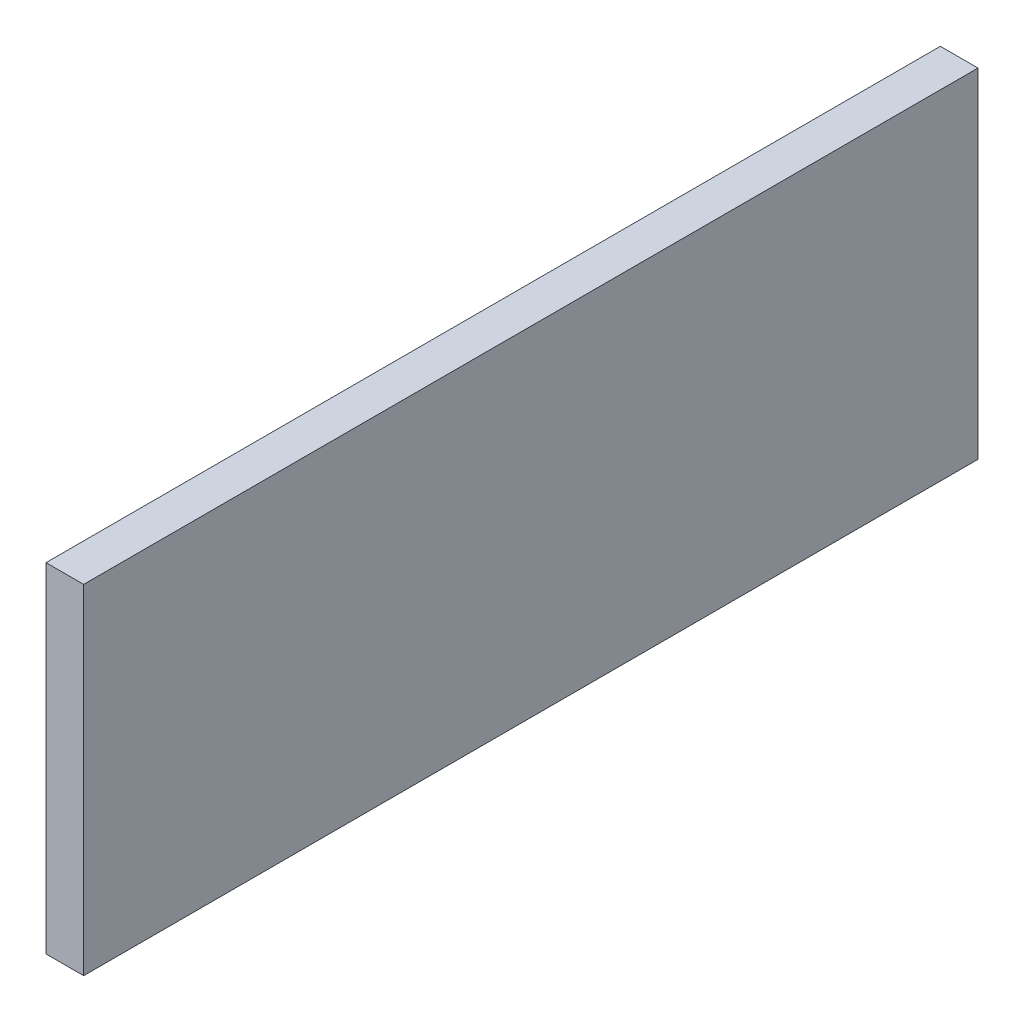
SolidWorks part; units mm, degrees
ref_plane "Front Plane" through (0, 0, 0) normal (0, 0, 1) x (1, 0, 0)
ref_plane "Top Plane" through (0, 0, 0) normal (0, 1, 0) x (1, 0, 0)
ref_plane "Right Plane" through (0, 0, 0) normal (1, 0, 0) x (0, 0, -1)
sketch "Sketch2" plane through (0, 0, 0) normal (1, 0, 0) x (0, 0, -1)
  line L1 (0, 0) -> (50, 0)
  line L2 (0, 0) -> (0, 22.5)
  line L3 (0, 22.5) -> (50, 22.5)
  line L4 (50, 0) -> (50, 22.5)
  dimension "D1" = 50
  dimension "D2" = 22.5
extrude "Boss-Extrude1" add sketch "Sketch2" along normal blind 10 contours L2 L3 L4 L1
sketch "Sketch4" plane through (0, 0, 0) normal (0, 0, 1) x (1, 0, 0)
  line L0 (5.325, 14.275) -> (5.325, 8.225) construction
  line L1 (7.05, 14.275) -> (7.05, 8.225)
  line L2 (3.6, 14.275) -> (3.6, 8.225)
  line L3 (0, 0) -> (0, 22.5) construction
  arc A0 (7.05, 14.275) -> (3.6, 14.275) centre (5.325, 14.275) ccw
  arc A1 (3.6, 8.225) -> (7.05, 8.225) centre (5.325, 8.225) ccw
  point P2 (5.325, 11.25)
  point P7 (3.6, 11.25)
  point P10 (0, 11.25)
  point P11 (5.325, 16)
  point P12 (5.325, 6.5)
  dimension "D3" = 3.45
  dimension "D4" = 9.5
  dimension "D1" = 0
  dimension "D2" = 3.6
extrude "USBC" cut sketch "Sketch4" against normal blind 10
sketch "Sketch5" plane through (0, 0, -50) normal (0, 0, -1) x (-1, 0, 0)
  line L0 (-5.225, 16.25) -> (-5.225, 6.25) construction
  line L1 (-3, 16.25) -> (-3, 6.25)
  line L2 (-7.45, 16.25) -> (-7.45, 6.25)
  line L3 (-10, 0) -> (-10, 22.5) construction
  line L5 (0, 0) -> (0, 22.5) construction
  arc A0 (-3, 16.25) -> (-7.45, 16.25) centre (-5.225, 16.25) ccw
  arc A1 (-7.45, 6.25) -> (-3, 6.25) centre (-5.225, 6.25) ccw
  point P2 (-5.225, 11.25)
  point P7 (-7.45, 11.25)
  point P10 (-10, 11.25)
  point P13 (-5.225, 4.025)
  point P14 (-5.225, 18.475)
  dimension "D4" = 14.45
  dimension "D3" = 4.45
  dimension "D1" = 0
  dimension "D2" = 3
extrude "POGO" cut sketch "Sketch5" against normal blind 10
sketch "Sketch6" plane through (10, 0, 0) normal (1, 0, 0) x (0, 0, -1)
  line L0 (0, 22.5) -> (50, 22.5) construction
  line L1 (1, 20.5) -> (49, 20.5)
  line L2 (1, 20.5) -> (1, 2)
  line L3 (1, 2) -> (49, 2)
  line L4 (49, 20.5) -> (49, 2)
  line L5 (0, 0) -> (0, 22.5) construction
  line L6 (0, 0) -> (50, 0) construction
  line L7 (50, 0) -> (50, 22.5) construction
  dimension "D1" = 2
  dimension "D2" = 1
  dimension "D3" = 2
  dimension "D4" = 1
extrude "Cut-Extrude3" cut sketch "Sketch6" against normal offset from surface (8 mm away) 2 up to face at (0, 11.25, -25)
sketch "Sketch7" plane through (10, 0, 0) normal (1, 0, 0) x (0, 0, -1)
  line L0 (1, 20.5) -> (1, 2) construction
  line L1 (1.25, 20.25) -> (48.75, 20.25)
  line L2 (1.25, 20.25) -> (1.25, 2.25)
  line L3 (1.25, 2.25) -> (48.75, 2.25)
  line L4 (48.75, 20.25) -> (48.75, 2.25)
  line L5 (49, 2) -> (49, 20.5) construction
  line L6 (1, 20.5) -> (49, 20.5) construction
  line L7 (49, 2) -> (1, 2) construction
  dimension "D1" = 0.25
  dimension "D2" = 0.25
  dimension "D3" = 0.25
  dimension "D4" = 0.25
extrude "Boss-Extrude2" add sketch "Sketch7" along normal blind 2 separate body
sketch "Sketch8" plane through (0, 0, 0) normal (0, 0, 1) x (1, 0, 0)
  line L0 (10, 0) -> (10, 22.5) construction
  line L1 (10, 22.5) -> (0, 22.5)
  line L2 (10, 22.5) -> (10, 0)
  line L3 (10, 0) -> (0, 0)
  line L4 (0, 22.5) -> (0, 0)
  line L5 (10, 22.5) -> (0, 22.5) construction
extrude "Cut-Extrude4" cut sketch "Sketch8" against normal through all
